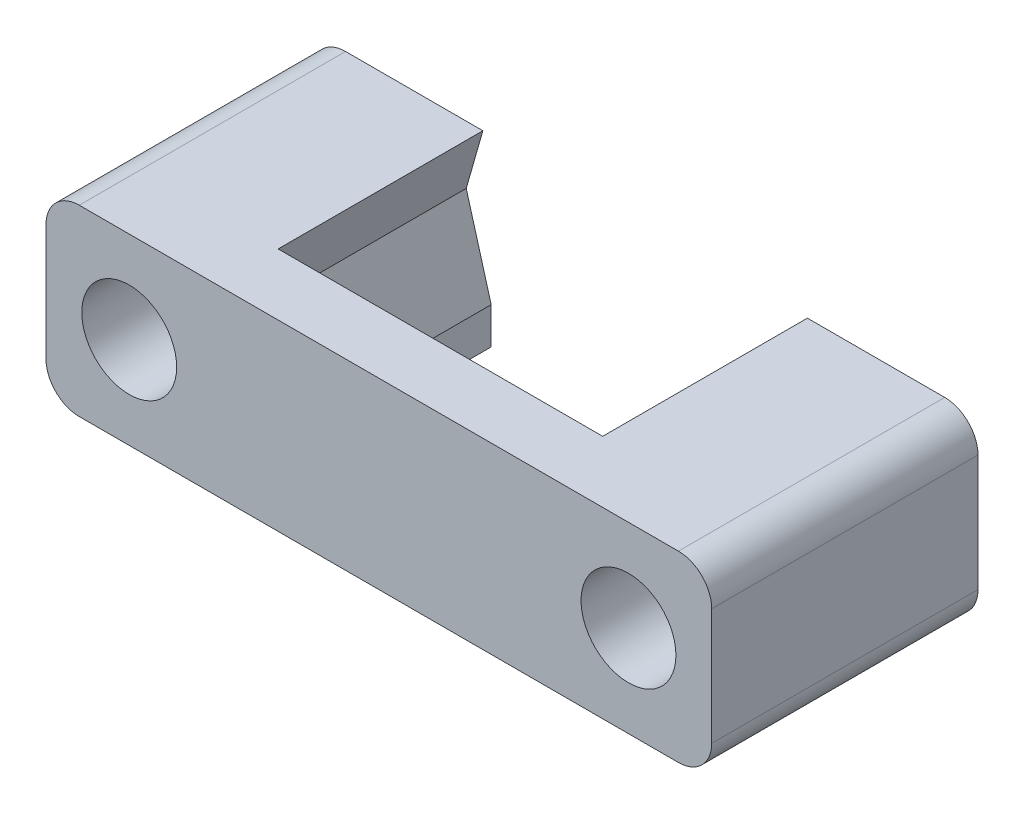
SolidWorks part; units mm, degrees
material "尼龙 101"
ref_plane "前视基准面" through (0, 0, 0) normal (0, 0, 1) x (1, 0, 0)
ref_plane "上视基准面" through (0, 0, 0) normal (0, 1, 0) x (1, 0, 0)
ref_plane "右视基准面" through (0, 0, 0) normal (1, 0, 0) x (0, 0, -1)
other "Configuration Table"
sketch "草图1" plane through (0, 0, 0) normal (0, 0, 1) x (1, 0, 0)
  line L1 (0, 0) -> (40, 0)
  line L2 (0, 0) -> (0, 11)
  line L3 (0, 11) -> (40, 11)
  line L4 (40, 0) -> (40, 11)
  circle A0 centre (5, 5.5) radius 1.6
  circle A1 centre (35, 5.5) radius 1.6
  dimension "D3" = 3.2
  dimension "D4" = 3.2
  dimension "D1" = 40
  dimension "D2" = 11
  dimension "D5" = 5
  dimension "D6" = 5.5
  dimension "D7" = 30
extrude "凸台-拉伸1" add sketch "草图1" along normal blind 14
sketch "草图2" plane through (0, 0, 0) normal (0, 0, -1) x (-1, 0, 0)
  line L0 (-29.75, 11) -> (-30.75, 7.5)
  line L1 (-40, 11) -> (0, 11) construction
  line L2 (-30.75, 7.5) -> (-29.75, 3.5)
  line L3 (-29.75, 3.5) -> (-29.75, 0)
  line L4 (0, 0) -> (-40, 0) construction
  line L5 (-20, 11) -> (-20, 0) construction
  line L6 (-10.25, 3.5) -> (-10.25, 0)
  line L7 (-9.25, 7.5) -> (-10.25, 3.5)
  line L8 (-10.25, 11) -> (-9.25, 7.5)
  line L9 (-10.25, 11) -> (-29.75, 11)
  line L10 (-29.75, 0) -> (-10.25, 0)
  line L11 (-10.75, 2.2) -> (-10.75, 0)
  line L12 (-9.25, 7.5) -> (-10.75, 2.2)
  line L13 (-29.25, 2.2) -> (-29.25, 0)
  line L14 (-30.75, 7.5) -> (-29.25, 2.2)
  line M9 (0, 11) -> (-40, 11)
  line M11 (-40, 0) -> (0, 0)
  dimension "D1" = 19.5
  dimension "D2" = 21.5
  dimension "D3" = 4
  dimension "D4" = 3.5
  dimension "D5" = 2.2
  dimension "D6" = 18.5
extrude "切除-拉伸1" cut sketch "草图2" against normal blind 10.3 contours L5 L11 L12 L8 M9 M11 | L5 L9 L0 L14 L13 L10
sketch "草图3" plane through (0, 0, 14) normal (0, 0, 1) x (1, 0, 0)
  circle A6 centre (5, 5.5) radius 2.85
  circle A7 centre (35, 5.5) radius 2.85
  dimension "D1" = 5.7
extrude "切除-拉伸2" cut sketch "草图3" against normal blind 5
sketch "草图4" plane through (0, 0, 0) normal (0, 0, -1) x (-1, 0, 0)
  line L0 (-10.25, 11) -> (-9.25, 7.5) construction
  line L3 (-10.75, 0) -> (0, 0) construction
  line L4 (0, 0) -> (0, 11) construction
  line L5 (0, 11) -> (-10.25, 11) construction
  line L8 (-30.75, 7.5) -> (-29.75, 11) construction
  line L9 (-29.75, 11) -> (-40, 11) construction
  line L10 (-40, 11) -> (-40, 0) construction
  line L11 (-40, 0) -> (-29.25, 0) construction
  line L12 (-10.25, 11) -> (-9.25, 7.5)
  line L15 (-10.75, 0) -> (0, 0)
  line L16 (0, 0) -> (0, 11)
  line L17 (0, 11) -> (-10.25, 11)
  line L20 (-30.75, 7.5) -> (-29.75, 11)
  line L21 (-29.75, 11) -> (-40, 11)
  line L22 (-40, 11) -> (-40, 0)
  line L23 (-40, 0) -> (-29.25, 0)
  line L24 (-9.25, 7.5) -> (-10.75, 2.2) construction
  line L25 (-10.75, 2.2) -> (-10.75, 0) construction
  line L26 (-29.25, 2.2) -> (-29.25, 0) construction
  line L27 (-30.75, 7.5) -> (-29.25, 2.2) construction
  line L28 (-9.25, 7.5) -> (-10.75, 2.2)
  line L29 (-10.75, 2.2) -> (-10.75, 0)
  line L30 (-29.25, 2.2) -> (-29.25, 0)
  line L31 (-30.75, 7.5) -> (-29.25, 2.2)
  circle A0 centre (-5, 5.5) radius 1.6 construction
  circle A1 centre (-35, 5.5) radius 1.6 construction
  circle A2 centre (-5, 5.5) radius 1.6
  circle A3 centre (-35, 5.5) radius 1.6
extrude "凸台-拉伸2" add sketch "草图4" along normal blind 2
fillet "圆角1" radius 2 4 edges at (0, 0, 6) (0, 11, 6) (40, 11, 6) (40, 0, 6)
